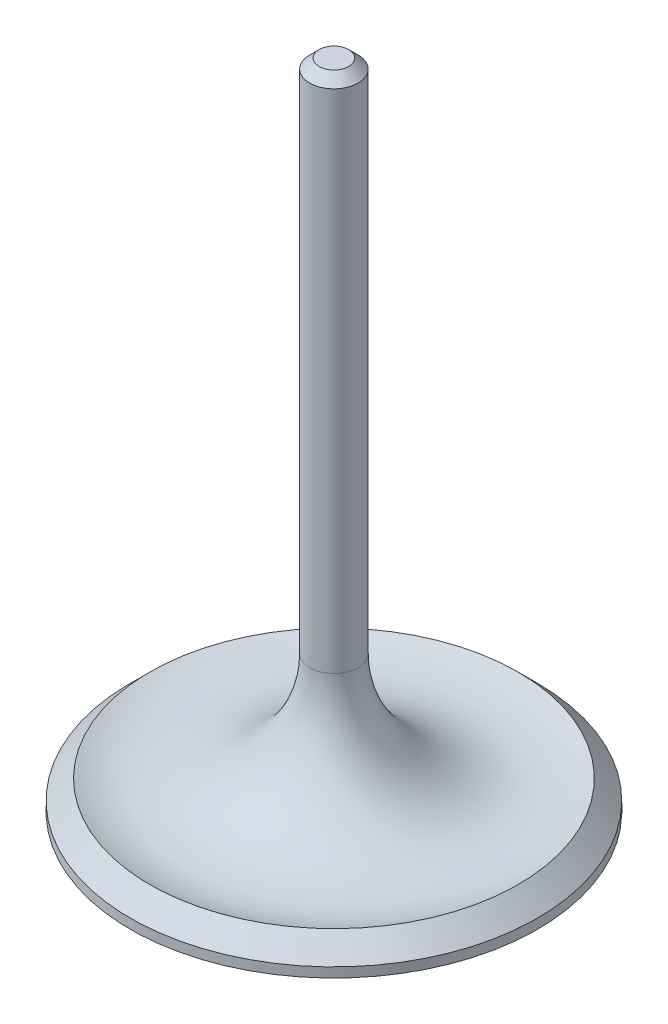
SolidWorks part; units mm, degrees
material "Brass"
ref_plane "Front Plane" through (0, 0, 0) normal (0, 0, 1) x (1, 0, 0)
ref_plane "Top Plane" through (0, 0, 0) normal (0, 1, 0) x (1, 0, 0)
ref_plane "Right Plane" through (0, 0, 0) normal (1, 0, 0) x (0, 0, -1)
sketch "Sketch1" plane through (0, 0, 0) normal (1, 0, 0) x (0, 0, -1)
  line L0 (0, 0) -> (0, 85.55)
  line L1 (0, 85.55) -> (3.18, 85.55)
  line L2 (3.18, 85.55) -> (3.18, 17.9547)
  line L3 (24.13, 3.81) -> (26.67, 1.27)
  line L4 (26.67, 1.27) -> (26.67, 0)
  line L5 (26.67, 0) -> (0, 0)
  arc A0 (3.18, 17.9547) -> (24.13, 3.81) centre (18.43, 17.9547) ccw
  dimension "D7" = 15.25
  dimension "D1" = 85.55
  dimension "D2" = 26.67
  dimension "D3" = 1.27
  dimension "D4" = 3.81
  dimension "D5" = 45
  dimension "D6" = 3.18
revolve "Revolve1" add sketch "Sketch1" angle 360 about L0
chamfer "Chamfer1" distance 1.25 angle 45 1 edges at (0, 85.55, -3.18)
